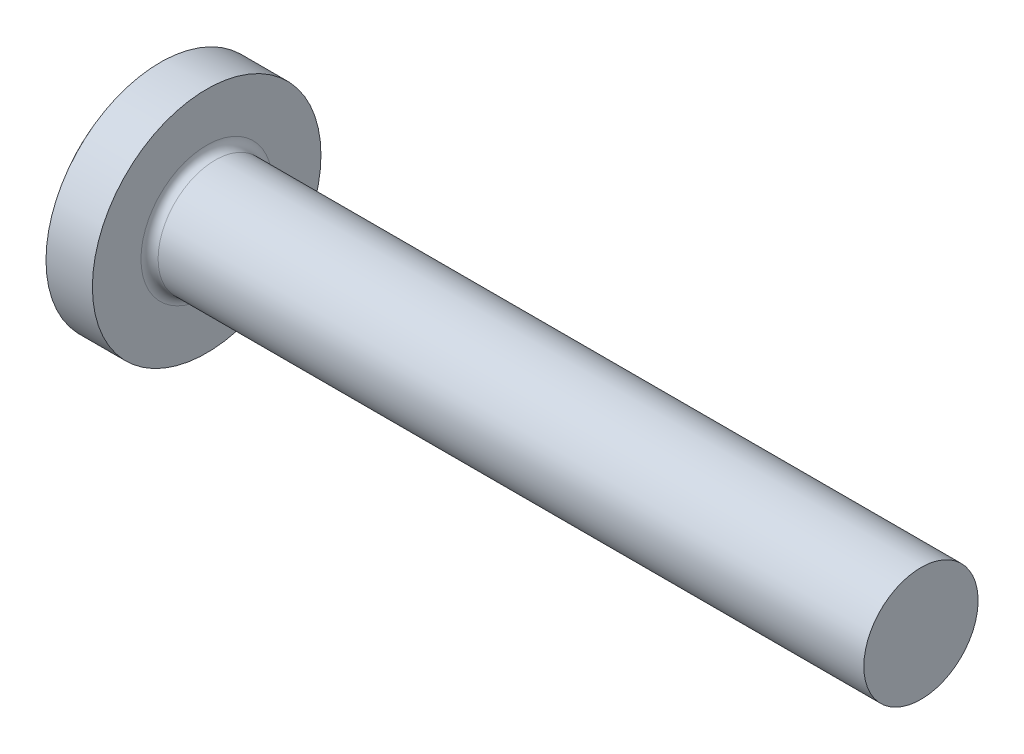
SolidWorks part; units mm, degrees
ref_plane "Front Plane" through (0, 0, 0) normal (0, 0, 1) x (1, 0, 0)
ref_plane "Top Plane" through (0, 0, 0) normal (0, 1, 0) x (1, 0, 0)
ref_plane "Right Plane" through (0, 0, 0) normal (1, 0, 0) x (0, 0, -1)
sketch "BodySke" plane through (0, 0, 0) normal (0, 0, 1) x (1, 0, 0)
  line L0 (0, 0) -> (111.3824, 0) construction
  line L1 (0, 0) -> (0, 8) construction
  line L2 (6, 4) -> (6, 8)
  line L3 (6, 8) -> (2.753, 8)
  line L4 (6, 4) -> (56, 4)
  line L5 (56, 4) -> (56, 0)
  line L6 (7.25, 7.824) -> (7.25, -6.8939) construction
  line L7 (0, 0) -> (56, 0)
  line L8 (8.5, 8.824) -> (8.5, -4.958) construction
  arc A1 (2.753, 8) -> (0, 0) centre (13, 0) ccw
  point P10 (56, 3.4455)
  dimension "Thread_minor" = 6.891
  dimension "Head_radius" = 13
  dimension "Diameter" = 8
  dimension "Head_height" = 6
  dimension "Advance" = 1.25
  dimension "Length" = 50
  dimension "Head_dia" = 16
  dimension "Thread_runout" = 2.5
revolve "BaseBody" add sketch "BodySke" angle 360 about L0
cosmetic thread "ThreadCosmetic" [suppressed] parameters "Thread_minor"=6.891
fillet "Fillet1" radius 0.6 1 edges at (6, 0, 4)
ref_plane "Plane1" through (4.5, 0, 0) normal (1, 0, 0) x (0, 0, -1)
sketch "RecSkeTop" plane through (0, 0, 0) normal (1, 0, 0) x (0, 0, -1)
  line L1 (-0.968, 4.4) -> (0.968, 4.4)
  line L2 (-0.968, 4.4) -> (-0.968, -4.4)
  line L3 (-0.968, -4.4) -> (0.968, -4.4)
  line L4 (0.968, 4.4) -> (0.968, -4.4)
  dimension "Cross_dia" = 8.8
  dimension "D1" = 4.4
  dimension "D2" = 1.936
  dimension "D3" = 0.968
sketch "RecSkeBot" plane through (4.5, 0, 0) normal (1, 0, 0) x (0, 0, -1)
  line L0 (-0.968, 4.4) -> (-0.968, -4.4) construction
  line L1 (-0.968, 2.1564) -> (0.968, 2.1564)
  line L2 (-0.968, 2.1564) -> (-0.968, -2.1564)
  line L3 (-0.968, -2.1564) -> (0.968, -2.1564)
  line L4 (0.968, 2.1564) -> (0.968, -2.1564)
  line L5 (0.968, 4.4) -> (0.968, -4.4) construction
  dimension "D1" = 4.3128
  dimension "D2" = 2.1564
loft "Recess" cut profiles "RecSkeTop", "RecSkeBot"
pattern_circular "RecPat" count 2 every 90 about axis through (0, 0, 0) along (1, 0, 0) of "Recess"
sketch "RecCorSke" plane through (0, 0, 0) normal (0, 0, 1) x (1, 0, 0)
  line L0 (0, 0) -> (57.5987, 0) construction
  line L1 (0, 0) -> (0, 2.1296)
  line L3 (0, 2.1296) -> (4.5, 1.8149)
  line L4 (4.5, 1.8149) -> (5.0897, 0)
  line L5 (5.0897, 0) -> (0, 0)
  dimension "D1" = 18
  dimension "D2" = 4.5
  dimension "D3" = 2.1296
  dimension "D4" = 4
revolve "RecessCore" cut sketch "RecCorSke" angle 360 about L0
sketch "ThdSchSke" plane through (0, 0, 0) normal (0, 0, 1) x (1, 0, 0)
  line L0 (0, 0) -> (55.1256, 0) construction
  line L1 (0, 0) -> (111.3824, 0) construction
  line L2 (55.6799, 4) -> (55.6799, 4.6403)
  line L3 (55.6799, 4.6403) -> (56.3201, 4.6403)
  line L4 (56.3201, 4.6403) -> (56.3201, 4)
  line L5 (56.3201, 4) -> (56, 3.4455)
  line L6 (56, 3.4455) -> (55.6799, 4)
  line L7 (6, 4) -> (56, 4) construction
  line L13 (56, 4) -> (56, 0) construction
revolve "ThreadSchematic" [suppressed] cut sketch "ThdSchSke" angle 360 about L0
pattern_linear "ThdSchPat" [suppressed] count 39 along (1, 0, 0)
equation "\"Thread_minor@ThreadCosmetic\" = \"Thread_minor@BodySke\""
equation "\"D1@RecSkeTop\" = \"Cross_dia@RecSkeTop\" / 2"
equation "\"D2@RecSkeTop\" = \"Cross_dia@RecSkeTop\" * 0.22"
equation "\"D3@RecSkeTop\" = \"D2@RecSkeTop\" / 2"
equation "\"D1@RecSkeBot\" = \"Cross_dia@RecSkeTop\" - 2 * \"Cross_depth@Plane1\" *  tan( 26.5 * 0.017453292 ) "
equation "\"D2@RecSkeBot\" = \"D1@RecSkeBot\" / 2"
equation "\"D2@RecCorSke\" = \"Cross_depth@Plane1\""
equation "\"D3@RecCorSke\" = \"D2@RecSkeTop\" * 1.1"
equation "\"Advance@ThdSchPat\" = \"Advance@BodySke\""
equation "\"D1@ThdSchPat\" =  int( ( \"Length@BodySke\"-\"Thread_runout@BodySke\" )  / \"Advance@ThdSchPat\" ) + 1 "
